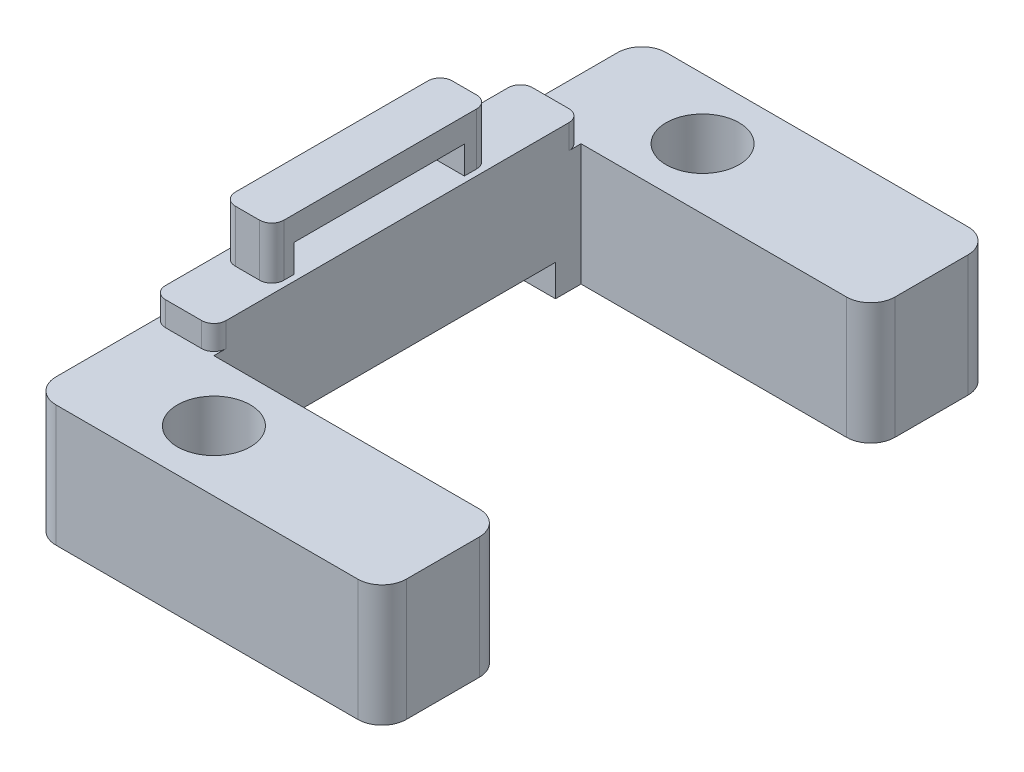
SolidWorks part; units mm, degrees
ref_plane "Front Plane" through (0, 0, 0) normal (0, 0, 1) x (1, 0, 0)
ref_plane "Top Plane" through (0, 0, 0) normal (0, 1, 0) x (1, 0, 0)
ref_plane "Right Plane" through (0, 0, 0) normal (1, 0, 0) x (0, 0, -1)
sketch "Sketch1" plane through (0, 0, 0) normal (0, 1, 0) x (1, 0, 0)
  line L0 (5.9584, 12.55) -> (-5.9584, 12.55)
  line L1 (5.9584, 7.55) -> (5.9584, 12.55)
  line L3 (-5.9584, 7.55) -> (5.9584, 7.55)
  line L4 (-5.9584, -7.55) -> (5.9584, -7.55)
  line L5 (5.9584, -7.55) -> (5.9584, -12.55)
  line L7 (5.9584, -12.55) -> (-5.9584, -12.55)
  line L8 (-5.9584, 12.55) -> (-8.4528, 12.55)
  line L9 (-8.4528, 12.55) -> (-8.4528, -12.55)
  line L10 (-8.4528, -12.55) -> (-5.9584, -12.55)
  line L11 (-5.9584, -7.55) -> (-5.9584, 7.55)
  circle A0 centre (-3.4584, -10.05) radius 1.5
  circle A1 centre (-3.4584, 10.05) radius 1.5
  dimension "D1" = 3
  dimension "D2" = 2.5
  dimension "D3" = 9.4167
extrude "Boss-Extrude1" add sketch "Sketch1" along normal blind 5
sketch "Sketch2" plane through (0, 5, 0) normal (0, 1, 0) x (1, 0, 0)
  line L0 (-5.9584, 7.55) -> (-8.4528, 7.55)
  line L1 (-8.4528, 12.55) -> (-8.4528, -12.55) construction
  line L2 (-8.4528, 7.55) -> (-8.4528, -7.55)
  line L3 (-8.4528, -7.55) -> (-5.9584, -7.55)
  line L4 (-5.9584, -7.55) -> (-5.9584, 7.55)
extrude "Boss-Extrude2" add sketch "Sketch2" along normal blind 1
sketch "Sketch3" plane through (-8.4528, 0, 0) normal (-1, 0, 0) x (0, 0, 1)
  line L0 (-6.5, 0) -> (6.5, 0)
  line L1 (-12.55, 0) -> (12.55, 0) construction
  line L2 (-6.5, 0) -> (-6.5, 1.3)
  line L3 (-6.5, 1.3) -> (6.5, 1.3)
  line L4 (6.5, 1.3) -> (6.5, 0)
  point P6 (0, 0)
  dimension "D1" = 13
  dimension "D2" = 1.3
extrude "Cut-Extrude1" cut sketch "Sketch3" against normal through all
sketch "Sketch4" plane through (0, 6, 0) normal (0, 1, 0) x (1, 0, 0)
  line L0 (-5.9584, 0) -> (-8.4528, 0) construction
  line L1 (-5.9584, -7.55) -> (-5.9584, 7.55) construction
  line L2 (-8.4528, 7.55) -> (-8.4528, -7.55) construction
  line L3 (-8.2056, -4) -> (-6.2056, -4)
  line L4 (-6.2056, -4) -> (-6.2056, -4.923)
  line L5 (-6.2056, -4.923) -> (-8.2056, -4.923)
  line L6 (-8.2056, -4.923) -> (-8.2056, -4)
  line L7 (-8.2056, 4) -> (-8.2056, 3)
  line L8 (-8.2056, 3) -> (-6.2056, 3)
  line L9 (-6.2056, 3) -> (-6.2056, 4)
  line L10 (-6.2056, 4) -> (-8.2056, 4)
  point P13 (-7.2056, -4)
  point P16 (-7.2056, 0)
  dimension "D1" = 4
  dimension "D2" = 4
  dimension "D3" = 1
  dimension "D4" = 2
  dimension "D5" = 2
extrude "Boss-Extrude3" add sketch "Sketch4" along normal blind 1.14
sketch "Sketch5" plane through (0, 7.14, 0) normal (0, 1, 0) x (1, 0, 0)
  line L0 (-8.2056, 4) -> (-8.2056, -4.923)
  line L1 (-8.2056, -4.923) -> (-6.2056, -4.923)
  line L2 (-6.2056, -4.923) -> (-6.2056, 4)
  line L3 (-6.2056, 4) -> (-8.2056, 4)
extrude "Boss-Extrude4" add sketch "Sketch5" along normal blind 1
fillet "Fillet1" radius 1 6 edges at (5.9584, 2.5, -7.55) (5.9584, 2.5, -12.55) (-8.4528, 2.5, -12.55) (-8.4528, 2.5, 12.55) (5.9584, 2.5, 7.55) (5.9584, 2.5, 12.55)
fillet "Fillet2" radius 0.5 8 edges at (-6.2056, 7.07, -4) (-8.2056, 7.07, -4) (-6.2056, 7.07, 4.923) (-8.2056, 7.07, 4.923) (-5.9584, 5.5, 7.55) (-8.4528, 5.5, 7.55) (-5.9584, 5.5, -7.55) (-8.4528, 5.5, -7.55)
